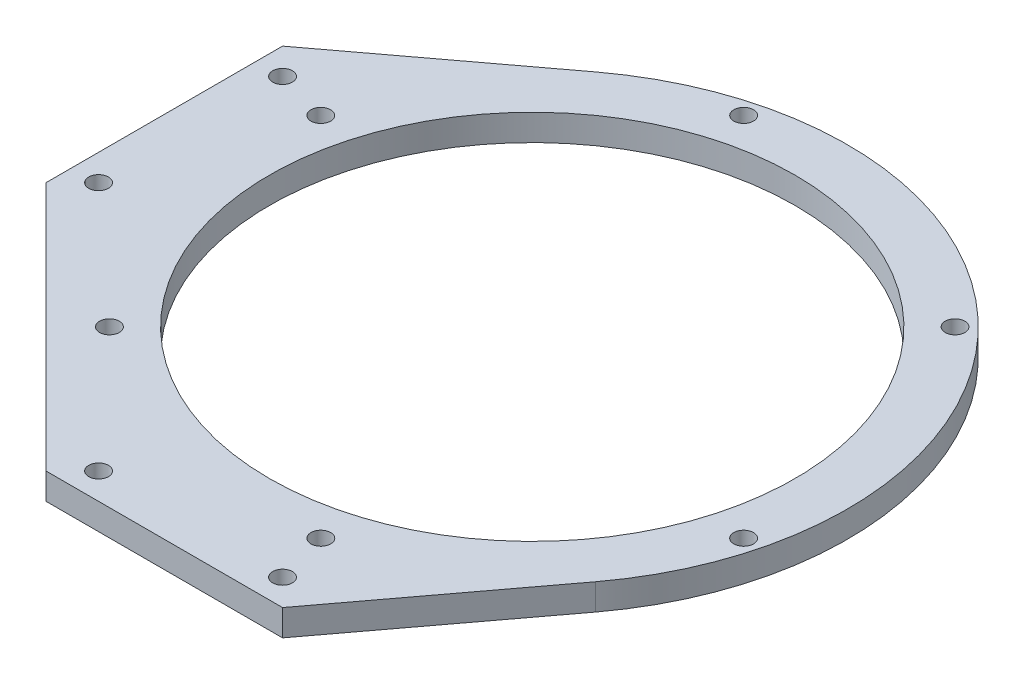
SolidWorks part; units mm, degrees
ref_plane "前视基准面" through (0, 0, 0) normal (0, 0, 1) x (1, 0, 0)
ref_plane "上视基准面" through (0, 0, 0) normal (0, 1, 0) x (1, 0, 0)
ref_plane "右视基准面" through (0, 0, 0) normal (1, 0, 0) x (0, 0, -1)
other "Configuration Table"
sketch "草图1" plane through (0, 0, 0) normal (0, 1, 0) x (1, 0, 0)
  line L0 (0, 0) -> (-40, 0) construction
  line L1 (-40, 0) -> (-56, 0) construction
  line L2 (-56, 18) -> (-56, -18)
  line L3 (-56, 18) -> (-28.8, 38.4)
  line L4 (0, 0) -> (0, -40) construction
  line L5 (0, -40) -> (-40, 0) construction
  line L6 (0, 0) -> (-20, -20) construction
  line L7 (18, -56) -> (38.4, -28.8)
  line L8 (18, -56) -> (-18, -56)
  line L9 (-56, -18) -> (-18, -56)
  line L10 (0, 0) -> (28.2843, 28.2843) construction
  line L11 (28.2843, 28.2843) -> (30.4056, 30.4056) construction
  line L12 (30.4056, 30.4056) -> (33.9411, 33.9411) construction
  line L13 (0, -48) -> (0, -56) construction
  line L14 (0, -52) -> (-14, -52) construction
  circle A0 centre (0, 0) radius 40
  arc A2 (-28.8, 38.4) -> (38.4, -28.8) centre (0, 0) cw
  circle A3 centre (0, 0) radius 43 construction
  circle A4 centre (32.1734, 32.1734) radius 1.5
  circle A5 centre (43.9496, -11.7763) radius 1.5
  circle A6 centre (11.7763, -43.9496) radius 1.5
  circle A7 centre (-32.1734, -32.1734) radius 1.5
  circle A8 centre (-43.9496, 11.7763) radius 1.5
  circle A9 centre (-11.7763, 43.9496) radius 1.5
  arc A10 (-28.8, 38.4) -> (36.4108, -31.2771) centre (0, 0) ccw construction
  circle A11 centre (-14, -52) radius 1.5
  circle A12 centre (14, -52) radius 1.5
  circle A13 centre (-52, -14) radius 1.5
  circle A14 centre (-52, 14) radius 1.5
  point P7 (-56, 0)
  point P32 (0, 0)
  dimension "D1" = 86
  dimension "D3" = 3
  dimension "D8" = 3
  dimension "D9" = 28
  dimension "D2" = 5
  dimension "D4" = 3
  dimension "D6" = 36
  dimension "D7" = 8
  dimension "D5" = 6
extrude "凸台-拉伸1" add sketch "草图1" along normal blind 4
